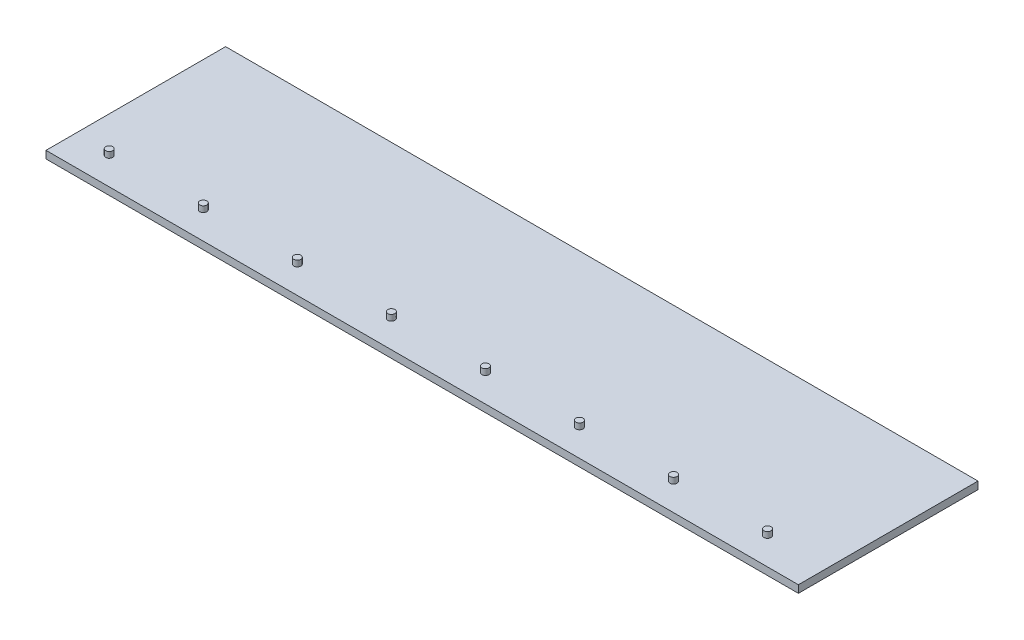
SolidWorks part; units mm, degrees
ref_plane "Front Plane" through (0, 0, 0) normal (0, 0, 1) x (1, 0, 0)
ref_plane "Top Plane" through (0, 0, 0) normal (0, 1, 0) x (1, 0, 0)
ref_plane "Right Plane" through (0, 0, 0) normal (1, 0, 0) x (0, 0, -1)
sketch "Sketch1" plane through (0, 0, 0) normal (0, 1, 0) x (1, 0, 0)
  line L1 (0, 0) -> (159.5929, 0)
  line L2 (0, 0) -> (0, 38.1)
  line L3 (0, 38.1) -> (159.5929, 38.1)
  line L4 (159.5929, 0) -> (159.5929, 38.1)
  dimension "D1" = 159.5929
  dimension "D2" = 38.1
extrude "Boss-Extrude1" add sketch "Sketch1" along normal blind 1.5875
sketch "Sketch2" plane through (0, 1.5875, 0) normal (0, 1, 0) x (1, 0, 0)
  line L0 (0, 5.7712) -> (7.6406, 5.7712)
  line L1 (0, 38.1) -> (0, 0) construction
  line L2 (0, 0) -> (159.5929, 0) construction
  circle A0 centre (7.6406, 5.7712) radius 0.75
  dimension "D1" = 1.5
  dimension "D2" = 5.7712
  dimension "D3" = 7.6406
extrude "Boss-Extrude2" add sketch "Sketch2" along normal blind 1.2446 contours A0
pattern_linear "LPattern1" count 8 spacing 19.9491 along (1, 0, 0) of "Boss-Extrude2"
